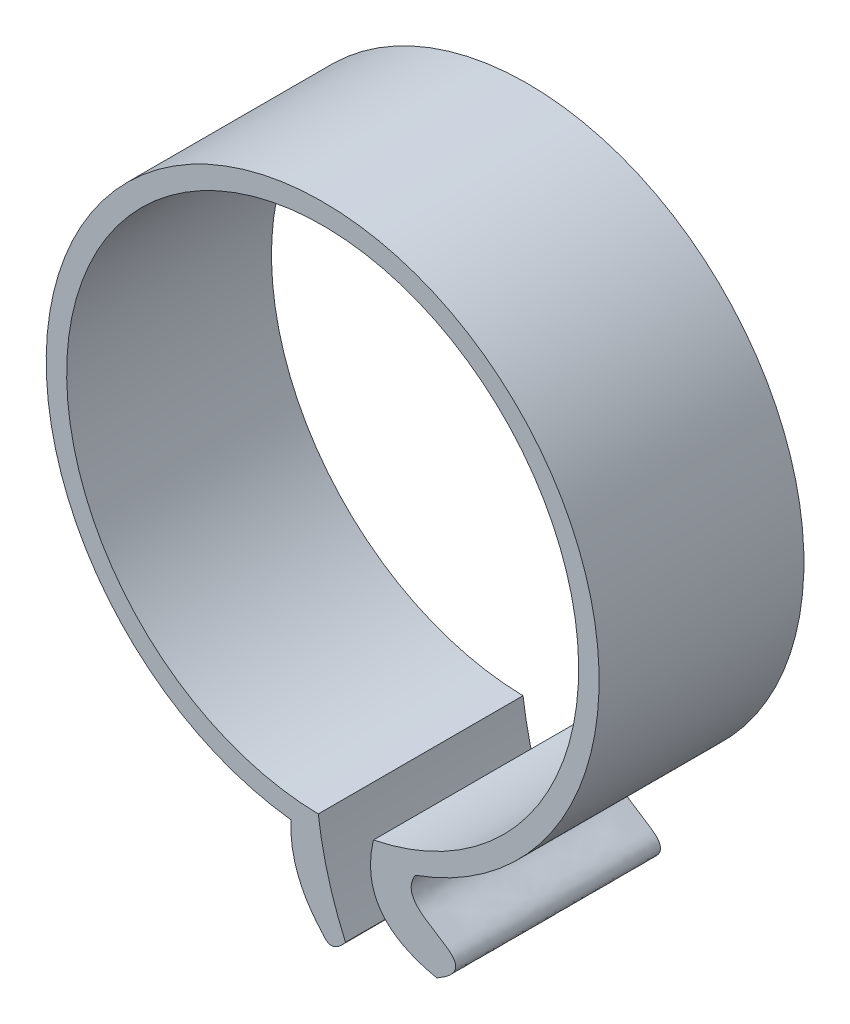
SolidWorks part; units mm, degrees
ref_plane "Front Plane" through (0, 0, 0) normal (0, 0, 1) x (1, 0, 0)
ref_plane "Top Plane" through (0, 0, 0) normal (0, 1, 0) x (1, 0, 0)
ref_plane "Right Plane" through (0, 0, 0) normal (1, 0, 0) x (0, 0, -1)
sketch "Sketch1" plane through (0, 0, 0) normal (0, 0, 1) x (1, 0, 0)
  arc A0 (2.4784, -12.2518) -> (-0.217, -12.4981) centre (0, 0) ccw
  arc A1 (4.524, -12.7194) -> (-1.556, -13.41) centre (0, 0) ccw
  spline S0 degree 2 poles (2.4784, -12.2518) (1.655, -15.7273) (5.5772, -16.5386) knots 0 0 0 1 1 1
  spline S1 degree 3 poles (4.524, -12.7194) (3.2532, -14.7466) (8.5492, -14.8421) (5.5772, -16.5386) knots 0 0 0 0 1 1 1 1
  spline S2 degree 2 poles (-0.217, -12.4981) (0.1035, -14.9951) (1.1154, -17.2604) knots 0 0 0 1 1 1
  spline S3 degree 2 poles (1.1154, -17.2604) (0.4346, -18.1086) (0, -17.4477) knots 0 0 0 1 1 1
  spline S4 degree 3 poles (0, -17.4477) (-1.0912, -16.2835) (-1.6098, -14.9376) (-1.556, -13.41) knots 0 0 0 0 0.825398 0.825398 0.825398 0.825398
  dimension "D2" = 27
  dimension "D1" = 25
extrude "Boss-Extrude1" add sketch "Sketch1" along normal blind 10
